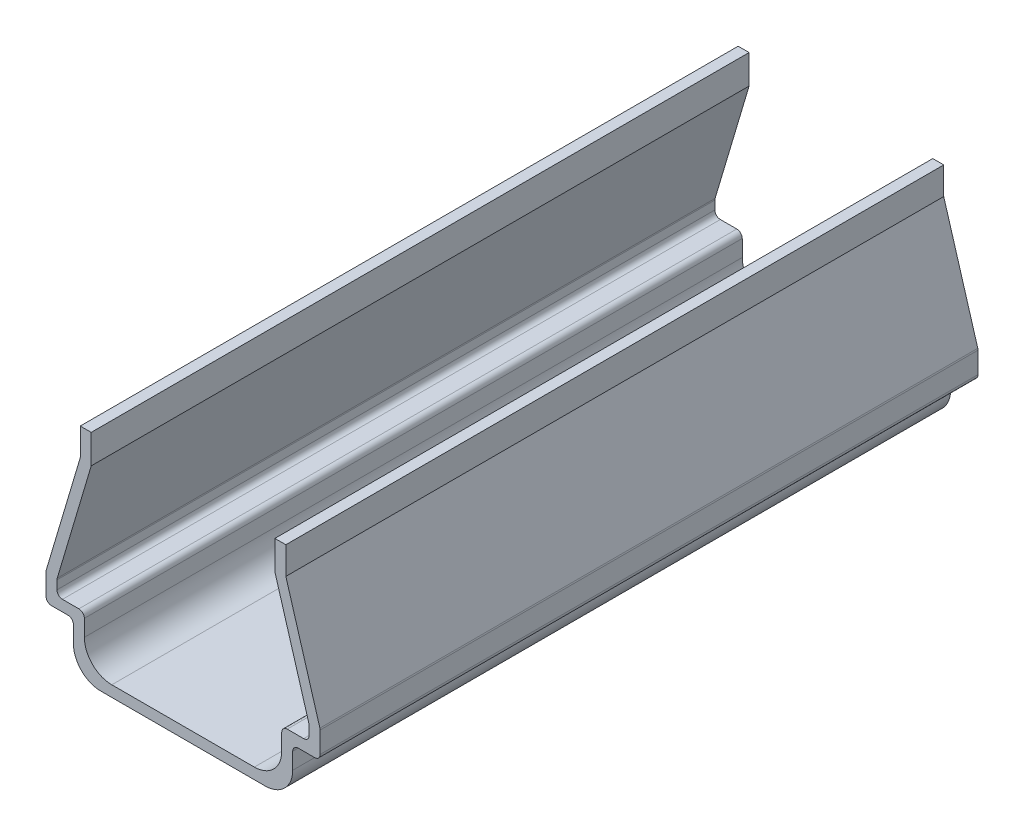
SolidWorks part; units mm, degrees
ref_plane "Front Plane" through (0, 0, 0) normal (0, 0, 1) x (1, 0, 0)
ref_plane "Top Plane" through (0, 0, 0) normal (0, 1, 0) x (1, 0, 0)
ref_plane "Right Plane" through (0, 0, 0) normal (1, 0, 0) x (0, 0, -1)
sketch "Sketch1" plane through (0, 0, 0) normal (0, 0, 1) x (1, 0, 0)
  line L0 (0, 0) -> (0, 7.1478) construction
  line L1 (4, 0) -> (-4, 0)
  line L2 (-4, 0) -> (-4, 1.8)
  line L3 (-4, 1.8) -> (-5, 1.8)
  line L4 (-5, 1.8) -> (-5, 2.8)
  line L5 (4, 0) -> (4, 1.8)
  line L6 (4, 1.8) -> (5, 1.8)
  line L7 (5, 1.8) -> (5, 2.8)
  line L8 (-5, 2.8) -> (-3.75, 7)
  line L9 (-3.75, 7) -> (-3.75, 8)
  line L10 (3.75, 7) -> (3.75, 8)
  line L11 (5, 2.8) -> (3.75, 7)
  dimension "D1" = 8
  dimension "D2" = 10
  dimension "D3" = 1.8
  dimension "D4" = 8
  dimension "D5" = 1
  dimension "D6" = 1
  dimension "D7" = 7.5
extrude "Extrude-Thin1" add sketch "Sketch1" along normal blind 24 thin
fillet "Fillet1" radius 1 4 edges at (3.6, 0.4, 12) (4, 0, 12) (-4, 0, 12) (-3.6, 0.4, 12)
fillet "Fillet2" radius 0.2 12 edges at (5, 2.8, 12) (4.6, 2.2, 12) (-4.6, 2.7417, 12) (-5, 2.8, 12) (-4.6, 2.2, 12) (5, 1.8, 12) (-5, 1.8, 12) (4.6, 2.7417, 12) (4, 1.8, 12) (3.6, 2.2, 12) (-4, 1.8, 12) (-3.6, 2.2, 12)
